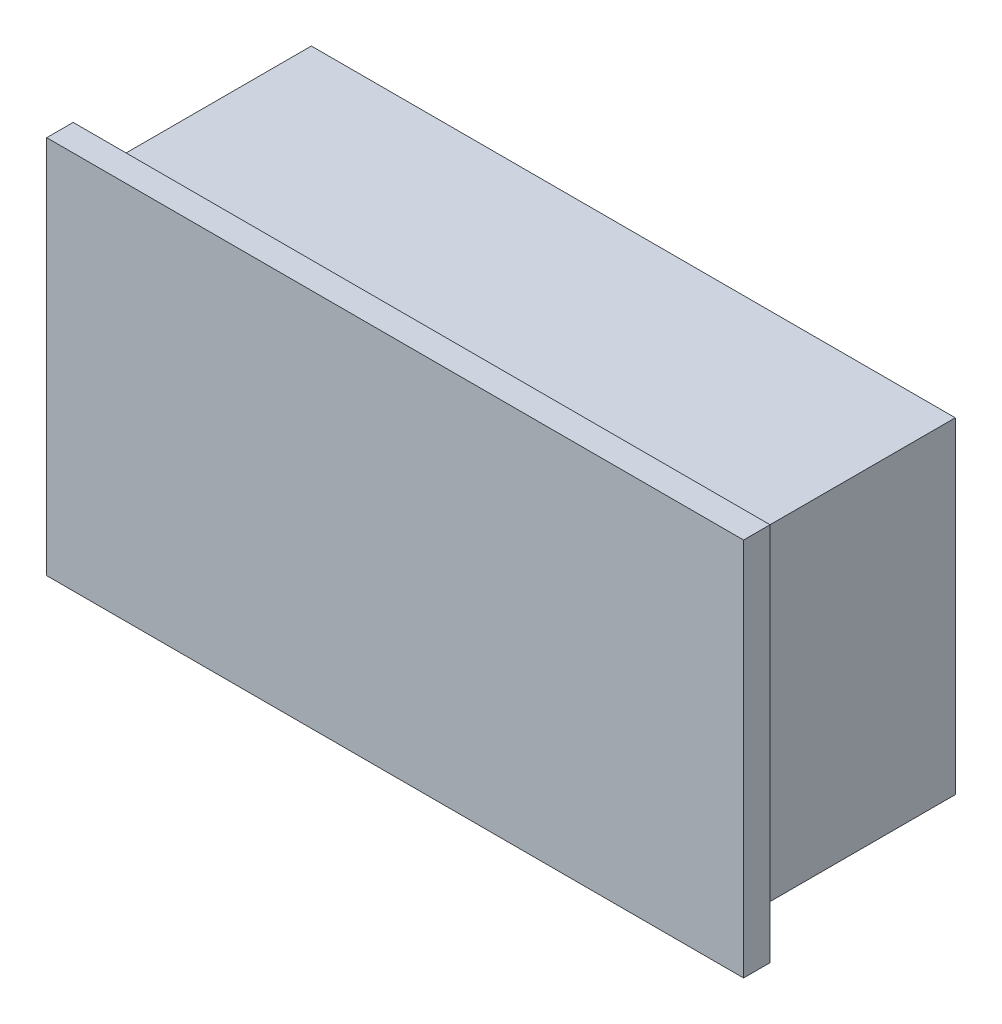
SolidWorks part; units mm, degrees
ref_plane "Ebene vorne" through (0, 0, 0) normal (0, 0, 1) x (1, 0, 0)
ref_plane "Ebene oben" through (0, 0, 0) normal (0, 1, 0) x (1, 0, 0)
ref_plane "Ebene rechts" through (0, 0, 0) normal (1, 0, 0) x (0, 0, -1)
sketch "Skizze1" plane through (0, 0, 0) normal (0, 0, 1) x (1, 0, 0)
  line L1 (-39.5, 21.5) -> (39.5, 21.5)
  line L2 (-39.5, 21.5) -> (-39.5, -21.5)
  line L3 (-39.5, -21.5) -> (39.5, -21.5)
  line L4 (39.5, 21.5) -> (39.5, -21.5)
  line L5 (-39.5, 21.5) -> (39.5, -21.5) construction
  line L6 (-39.5, -21.5) -> (39.5, 21.5) construction
  point P0 (0, 0)
  dimension "D1" = 79
  dimension "D2" = 43
extrude "Aufsatz-Linear austragen1" add sketch "Skizze1" along normal blind 27
sketch "Skizze2" plane through (0, 0, 0) normal (0, 0, -1) x (-1, 0, 0)
  line L1 (36.5, 18.5) -> (-36.5, 18.5)
  line L2 (36.5, 18.5) -> (36.5, -18.5)
  line L3 (36.5, -18.5) -> (-36.5, -18.5)
  line L4 (-36.5, 18.5) -> (-36.5, -18.5)
  line L5 (36.5, 18.5) -> (-36.5, -18.5) construction
  line L6 (36.5, -18.5) -> (-36.5, 18.5) construction
  line L7 (39.5, -21.5) -> (-39.5, -21.5)
  line L8 (39.5, -21.5) -> (39.5, 21.5)
  line L9 (39.5, 21.5) -> (-39.5, 21.5)
  line L10 (-39.5, -21.5) -> (-39.5, 21.5)
  line L11 (39.5, -21.5) -> (-39.5, 21.5) construction
  line L12 (39.5, 21.5) -> (-39.5, -21.5) construction
  point P0 (0, 0)
  point P6 (0, 0)
  dimension "D1" = 3
  dimension "D2" = 3
extrude "Schnitt-Linear austragen1" cut sketch "Skizze2" against normal offset from surface (24 mm away) 3 up to face at (0, 0, 27)
